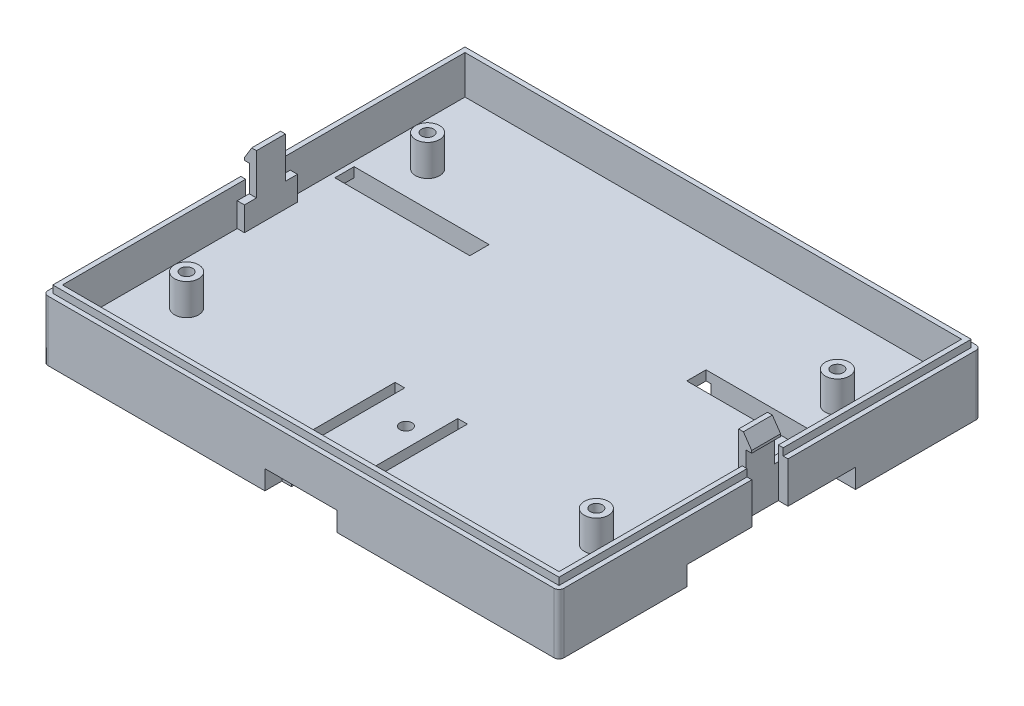
SolidWorks part; units mm, degrees
ref_plane "Front Plane" through (0, 0, 0) normal (0, 0, 1) x (1, 0, 0)
ref_plane "Top Plane" through (0, 0, 0) normal (0, 1, 0) x (1, 0, 0)
ref_plane "Right Plane" through (0, 0, 0) normal (1, 0, 0) x (0, 0, -1)
sketch "Sketch1" plane through (0, 0, 0) normal (0, 1, 0) x (1, 0, 0)
  line L0 (52.5, -43.75) -> (-52.5, -43.75)
  line L1 (-53.5, -42.75) -> (-53.5, 42.75)
  line L2 (-52.5, 43.75) -> (52.5, 43.75)
  line L3 (53.5, 42.75) -> (53.5, -42.75)
  arc A0 (52.5, -43.75) -> (53.5, -42.75) centre (52.5, -42.75) ccw
  arc A1 (-53.5, -42.75) -> (-52.5, -43.75) centre (-52.5, -42.75) ccw
  arc A2 (-52.5, 43.75) -> (-53.5, 42.75) centre (-52.5, 42.75) ccw
  arc A3 (53.5, 42.75) -> (52.5, 43.75) centre (52.5, 42.75) ccw
extrude "Boss-Extrude1" add sketch "Sketch1" along normal blind 12.5
sketch "Sketch2" plane through (0, 0, 0) normal (0, -1, 0) x (1, 0, 0)
  line L0 (-52.5, 43.75) -> (52.5, 43.75) construction
  line L1 (-51.5, -41.75) -> (51.5, -41.75)
  line L2 (-51.5, -41.75) -> (-51.5, 41.75)
  line L3 (-51.5, 41.75) -> (51.5, 41.75)
  line L4 (51.5, -41.75) -> (51.5, 41.75)
  line L5 (-53.5, -42.75) -> (-53.5, 42.75) construction
  line L6 (53.5, 42.75) -> (53.5, -42.75) construction
  line L7 (52.5, -43.75) -> (-52.5, -43.75) construction
  dimension "D1" = 2
  dimension "D2" = 2
  dimension "D3" = 2
  dimension "D4" = 2
extrude "Cut-Extrude1" cut sketch "Sketch2" against normal blind 4
sketch "Sketch3" plane through (0, 12.5, 0) normal (0, 1, 0) x (1, 0, 0)
  line L0 (-53.5, 42.75) -> (-53.5, -42.75) construction
  line L1 (-51.5, -41.75) -> (51.5, -41.75)
  line L2 (-51.5, -41.75) -> (-51.5, 41.75)
  line L3 (-51.5, 41.75) -> (51.5, 41.75)
  line L4 (51.5, -41.75) -> (51.5, 41.75)
  line L5 (52.5, 43.75) -> (-52.5, 43.75) construction
  line L6 (53.5, -42.75) -> (53.5, 42.75) construction
  line L7 (-52.5, -43.75) -> (52.5, -43.75) construction
  dimension "D1" = 2
  dimension "D2" = 2
  dimension "D3" = 2
  dimension "D4" = 2
extrude "Cut-Extrude2" cut sketch "Sketch3" against normal blind 6.5
sketch "Sketch4" plane through (0, 12.5, 0) normal (0, 1, 0) x (1, 0, 0)
  line L0 (-52.5, -43.75) -> (52.5, -43.75) construction
  line L1 (-51.5, 41.75) -> (51.5, 41.75)
  line L2 (-51.5, 41.75) -> (-51.5, -41.75)
  line L3 (-51.5, -41.75) -> (51.5, -41.75)
  line L4 (51.5, 41.75) -> (51.5, -41.75)
  line L5 (52.5, -42.75) -> (-52.5, -42.75)
  line L6 (52.5, -42.75) -> (52.5, 42.75)
  line L7 (52.5, 42.75) -> (-52.5, 42.75)
  line L8 (-52.5, -42.75) -> (-52.5, 42.75)
  dimension "D1" = 1
  dimension "D2" = 1
  dimension "D3" = 1
  dimension "D4" = 1
extrude "Boss-Extrude2" add sketch "Sketch4" along normal blind 1.5
sketch "Sketch7" plane through (-53.5, 0, 0) normal (-1, 0, 0) x (0, 0, 1)
  line L0 (-42.75, 0) -> (42.75, 0) construction
  line L1 (-17.75, 0) -> (17.25, 0)
  line L2 (-17.75, 0) -> (-17.75, 4)
  line L4 (17.25, 0) -> (17.25, 4)
  line L11 (-17.75, 4) -> (17.25, 4)
  dimension "D1" = 4
  dimension "D2" = 35
  dimension "D3" = 25
extrude "Cut-Extrude3" cut sketch "Sketch7" against normal through all
sketch "Sketch8" plane through (-53.5, 0, 0) normal (-1, 0, 0) x (0, 0, 1)
  line L0 (17.25, 4) -> (-17.75, 4) construction
  line L1 (-3.75, 4) -> (3.75, 4)
  line L2 (-3.75, 4) -> (-3.75, 14)
  line L3 (-3.75, 14) -> (3.75, 14)
  line L4 (3.75, 4) -> (3.75, 14)
  line L5 (-42.75, 14) -> (42.75, 14) construction
  dimension "D1" = 7.5
  dimension "D2" = 14
extrude "Cut-Extrude4" cut sketch "Sketch8" against normal blind 2
sketch "Sketch9" plane through (53.5, 0, 0) normal (1, 0, 0) x (0, 0, -1)
  line L2 (-3.75, 14) -> (-3.75, 4)
  line L3 (-3.75, 4) -> (3.75, 4)
  line L4 (-3.75, 14) -> (3.75, 14)
  line L5 (3.75, 4) -> (3.75, 14)
extrude "Cut-Extrude5" cut sketch "Sketch9" against normal blind 2
sketch "Sketch10" plane through (51.5, 0, 0) normal (-1, 0, 0) x (0, 0, 1)
  line L0 (41.75, 6) -> (3.75, 6) construction
  line L1 (5.5, 6) -> (-5.5, 6)
  line L2 (5.5, 6) -> (5.5, 11)
  line L4 (-5.5, 6) -> (-5.5, 11)
  line L5 (-3, 11) -> (-3, 16.5)
  line L6 (-3, 16.5) -> (3, 16.5)
  line L7 (3, 16.5) -> (3, 11)
  line L8 (-3.75, 12.5) -> (-3.75, 4) construction
  line L9 (-5.5, 11) -> (-3, 11)
  line L10 (3, 11) -> (5.5, 11)
  dimension "D1" = 11
  dimension "D2" = 1.75
  dimension "D3" = 5
  dimension "D4" = 6
  dimension "D5" = 0.75
  dimension "D6" = 5.5
  dimension "D7" = 5
extrude "Boss-Extrude3" add sketch "Sketch10" along normal blind 1.5
sketch "Sketch11" plane through (-51.5, 0, 0) normal (1, 0, 0) x (0, 0, -1)
  line L0 (-3.75, 14) -> (-42.75, 14) construction
  line L8 (-5.5, 11) -> (-5.5, 6)
  line L9 (-3, 11) -> (-5.5, 11)
  line L10 (-3, 16.5) -> (-3, 11)
  line L11 (3, 16.5) -> (-3, 16.5)
  line L12 (3, 11) -> (3, 16.5)
  line L13 (5.5, 11) -> (3, 11)
  line L14 (5.5, 6) -> (5.5, 11)
  line L15 (-5.5, 6) -> (5.5, 6)
  line L16 (-5.5, 11) -> (-5.5, 6)
  line L17 (-3, 11) -> (-5.5, 11)
  line L18 (-3, 16.5) -> (-3, 11)
  line L19 (3, 16.5) -> (-3, 16.5)
  line L20 (3, 11) -> (3, 16.5)
  line L21 (5.5, 11) -> (3, 11)
  line L22 (5.5, 6) -> (5.5, 11)
  line L23 (-5.5, 6) -> (5.5, 6)
  dimension "D1" = 0
extrude "Boss-Extrude4" add sketch "Sketch11" along normal blind 1.5
sketch "Sketch12" plane through (0, 0, -3) normal (0, 0, -1) x (-1, 0, 0)
  line L0 (-52.7206, 16.5) -> (-50, 16.5)
  line L1 (-52.7206, 16.5) -> (-52.7206, 17)
  line L2 (-50, 16.5) -> (-50, 19.5)
  line L3 (-50, 19.5) -> (-51, 19.5)
  line L4 (-52.7206, 17) -> (-51, 19.5)
  dimension "D1" = 3
  dimension "D2" = 1
  dimension "D3" = 0.5
extrude "Boss-Extrude5" add sketch "Sketch12" against normal up to surface (6 mm away) up to face at (50.75, 13.75, 3)
sketch "Sketch13" plane through (0, 0, -3) normal (0, 0, -1) x (-1, 0, 0)
  line L0 (50, 16.5) -> (52.5, 16.5)
  line L1 (52.5, 16.5) -> (52.5, 17)
  line L2 (50, 16.5) -> (50, 19.5)
  line L3 (50, 19.5) -> (51, 19.5)
  line L4 (51, 19.5) -> (52.5, 17)
  dimension "D2" = 0.5
  dimension "D3" = 3
  dimension "D4" = 1
extrude "Boss-Extrude6" add sketch "Sketch13" against normal up to surface (6 mm away) up to face at (-50.75, 13.75, 3)
sketch "Sketch14" plane through (0, 4, 0) normal (0, -1, 0) x (1, 0, 0)
  line L0 (-53.5, -3.75) -> (-53.5, -17.75) construction
  line L1 (50.5, -17.75) -> (22.5, -17.75)
  line L2 (50.5, -17.75) -> (50.5, -13.75)
  line L3 (50.5, -13.75) -> (22.5, -13.75)
  line L4 (22.5, -17.75) -> (22.5, -13.75)
  line L5 (-50.5, -17.75) -> (-22.5, -17.75)
  line L6 (-50.5, -17.75) -> (-50.5, -13.75)
  line L7 (-50.5, -13.75) -> (-22.5, -13.75)
  line L8 (-22.5, -17.75) -> (-22.5, -13.75)
  line L9 (53.5, -3.75) -> (53.5, -17.75) construction
  dimension "D1" = 3
  dimension "D2" = 3
  dimension "D3" = 4
  dimension "D4" = 28
  dimension "D5" = 28
  dimension "D6" = 4
extrude "Cut-Extrude6" cut sketch "Sketch14" against normal up to surface (2 mm away) up to face at (0, 6, 0)
sketch "Sketch15" plane through (0, 0, 0) normal (0, -1, 0) x (1, 0, 0)
  line L0 (-52.5, 43.75) -> (52.5, 43.75) construction
  line L1 (-7.5, 40.25) -> (7.5, 40.25)
  line L2 (-7.5, 40.25) -> (-7.5, 43.75)
  line L3 (-7.5, 43.75) -> (7.5, 43.75)
  line L4 (7.5, 40.25) -> (7.5, 43.75)
  dimension "D1" = 15
  dimension "D2" = 3.5
  dimension "D3" = 45
extrude "Cut-Extrude7" cut sketch "Sketch15" against normal blind 4
sketch "Sketch16" plane through (0, 6, 0) normal (0, 1, 0) x (1, 0, 0)
  line L0 (51.5, -41.75) -> (51.5, -5.5) construction
  line L1 (7.5, -40.75) -> (5.5, -40.75)
  line L2 (7.5, -40.75) -> (7.5, -16.75)
  line L3 (7.5, -16.75) -> (5.5, -16.75)
  line L4 (5.5, -40.75) -> (5.5, -16.75)
  line L5 (-51.5, -41.75) -> (51.5, -41.75) construction
  line L6 (-51.5, -3.75) -> (-51.5, -41.75) construction
  line L7 (-7.5, -40.75) -> (-5.5, -40.75)
  line L8 (-7.5, -40.75) -> (-7.5, -16.75)
  line L9 (-7.5, -16.75) -> (-5.5, -16.75)
  line L10 (-5.5, -40.75) -> (-5.5, -16.75)
  circle A0 centre (1.5, -23.5) radius 1.25
  dimension "D7" = 2.5
  dimension "D1" = 24
  dimension "D2" = 2
  dimension "D3" = 44
  dimension "D4" = 1
  dimension "D5" = 2
  dimension "D6" = 44
  dimension "D8" = 18.25
  dimension "D9" = 4
extrude "Cut-Extrude8" cut sketch "Sketch16" against normal up to surface (2 mm away) up to face at (0, 4, 7.0417)
sketch "Sketch17" plane through (0, 6, 0) normal (0, 1, 0) x (1, 0, 0)
  line L0 (51.5, 41.75) -> (-51.5, 41.75) construction
  line L1 (51.5, 3.75) -> (51.5, 41.75) construction
  line L2 (-51.5, 41.75) -> (-51.5, 5.5) construction
  line L3 (42.5, 25) -> (-42.5, 25) construction
  line L4 (42.5, 25) -> (42.5, -25) construction
  line L5 (42.5, -25) -> (-42.5, -25) construction
  line L6 (-42.5, 25) -> (-42.5, -25) construction
  line L7 (-51.5, -41.75) -> (51.5, -41.75) construction
  circle A0 centre (42.5, 25) radius 2.5
  circle A1 centre (42.5, -25) radius 2.5
  circle A2 centre (-42.5, 25) radius 2.5
  circle A3 centre (-42.5, -25) radius 2.5
  circle A4 centre (42.5, -25) radius 1.25
  circle A5 centre (42.5, 25) radius 1.25
  circle A6 centre (-42.5, 25) radius 1.25
  circle A7 centre (-42.5, -25) radius 1.25
  dimension "D1" = 5
  dimension "D6" = 5
  dimension "D7" = 5
  dimension "D8" = 5
  dimension "D9" = 2.5
  dimension "D10" = 2.5
  dimension "D11" = 2.5
  dimension "D12" = 2.5
  dimension "D2" = 16.75
  dimension "D3" = 9
  dimension "D4" = 9
  dimension "D5" = 16.75
extrude "Boss-Extrude7" add sketch "Sketch17" along normal blind 6.5
sketch "Sketch18" plane through (0, 4, 0) normal (0, -1, 0) x (1, 0, 0)
  line L1 (-51.5, -17.75) -> (-23.5, -17.75)
  line L2 (-51.5, -17.75) -> (-51.5, -19.75)
  line L3 (-51.5, -19.75) -> (-23.5, -19.75)
  line L4 (-23.5, -17.75) -> (-23.5, -19.75)
  line L5 (51.5, -17.75) -> (23.5, -17.75)
  line L6 (51.5, -17.75) -> (51.5, -19.75)
  line L7 (51.5, -19.75) -> (23.5, -19.75)
  line L8 (23.5, -17.75) -> (23.5, -19.75)
  dimension "D1" = 2
  dimension "D2" = 28
  dimension "D3" = 2
  dimension "D4" = 28
extrude "Boss-Extrude8" add sketch "Sketch18" along normal up to surface (4 mm away) up to face at (0, 0, -32.7914)
sketch "Sketch19" plane through (23.5, 0, 0) normal (-1, 0, 0) x (0, 0, 1)
  line L0 (-17.75, 0) -> (-14.75, 0)
  line L1 (-14.75, 0) -> (-14.75, 1)
  line L2 (-14.75, 1) -> (-15.75, 2)
  line L3 (-15.75, 2) -> (-17.75, 2)
  line L4 (-17.75, 4) -> (-17.75, 0) construction
  line L5 (-17.75, 2) -> (-17.75, 0)
  dimension "D1" = 3
  dimension "D2" = 1
  dimension "D3" = 2
  dimension "D4" = 2
extrude "Boss-Extrude9" add sketch "Sketch19" against normal blind 26
sketch "Sketch20" plane through (-23.5, 0, 0) normal (1, 0, 0) x (0, 0, -1)
  line L1 (14.75, 0) -> (14.75, 1) construction
  line L2 (14.75, 1) -> (15.75, 2) construction
  line L3 (15.75, 2) -> (17.75, 2) construction
  line L4 (14.75, 0) -> (17.75, 0)
  line L5 (14.75, 0) -> (14.75, 1)
  line L6 (14.75, 1) -> (15.75, 2)
  line L7 (15.75, 2) -> (17.75, 2)
  line L8 (17.75, 0) -> (17.75, 2)
extrude "Boss-Extrude10" add sketch "Sketch20" against normal blind 26
sketch "Sketch21" plane through (0, 4, 0) normal (0, -1, 0) x (1, 0, 0)
  line L0 (7.5, 41.75) -> (7.5, 17.75)
  line L1 (7.5, 16.75) -> (7.5, 40.75) construction
  line L2 (7.5, 17.75) -> (40.5, 17.75)
  line L4 (39.96, 19.75) -> (9.5, 19.75)
  line L5 (9.5, 19.75) -> (9.5, 41.75)
  line L6 (51.5, 41.75) -> (7.5, 41.75) construction
  line L7 (9.5, 41.75) -> (7.5, 41.75)
  line L8 (-7.5, 41.75) -> (-7.5, 17.75)
  line L9 (-7.5, 40.75) -> (-7.5, 16.75) construction
  line L10 (-7.5, 17.75) -> (-40.5, 17.75)
  line L12 (-39.96, 19.75) -> (-9.5, 19.75)
  line L13 (-9.5, 19.75) -> (-9.5, 41.75)
  line L14 (-7.5, 41.75) -> (-51.5, 41.75) construction
  line L15 (-9.5, 41.75) -> (-7.5, 41.75)
  line L16 (40.5, 17.75) -> (43.4964, 19.48)
  line L17 (39.96, 19.75) -> (42.4975, 21.215)
  line L18 (-40.5, 17.75) -> (-43.4964, 19.48)
  line L19 (-39.96, 19.75) -> (-42.4975, 21.215)
  line L20 (-42.4975, 21.215) -> (-43.4964, 19.48)
  line L21 (42.4975, 21.215) -> (43.4964, 19.48)
  dimension "D1" = 2
  dimension "D2" = 2
  dimension "D3" = 22
  dimension "D4" = 2
  dimension "D5" = 33
  dimension "D6" = 30.46
  dimension "D7" = 33
  dimension "D8" = 30.46
  dimension "D9" = 3.46
  dimension "D10" = 2.93
  dimension "D11" = 3.46
  dimension "D12" = 2.93
extrude "Boss-Extrude11" add sketch "Sketch21" along normal up to surface (4 mm away) up to face at (39.6724, 0, 35.4939)
sketch "Sketch22" plane through (7.5, 0, 0) normal (-1, 0, 0) x (0, 0, 1)
  line L0 (17.25, 0) -> (42.75, 0) construction
  line L1 (40.25, 0) -> (18, 0)
  line L2 (40.25, 0) -> (40.25, 2)
  line L3 (40.25, 2) -> (18, 2)
  line L4 (18, 0) -> (18, 2)
  dimension "D1" = 3.5
  dimension "D2" = 0.25
  dimension "D3" = 2
extrude "Boss-Extrude12" add sketch "Sketch22" along normal blind 2
sketch "Sketch23" plane through (-7.5, 0, 0) normal (1, 0, 0) x (0, 0, -1)
  line L4 (-40.25, 2) -> (-40.25, 0)
  line L5 (-18, 2) -> (-40.25, 2)
  line L6 (-18, 0) -> (-18, 2)
  line L7 (-40.25, 0) -> (-18, 0)
  line L8 (-40.25, 2) -> (-40.25, 0)
  line L9 (-18, 2) -> (-40.25, 2)
  line L10 (-18, 0) -> (-18, 2)
  line L11 (-40.25, 0) -> (-18, 0)
  dimension "D1" = 0
extrude "Boss-Extrude13" add sketch "Sketch23" along normal blind 2
